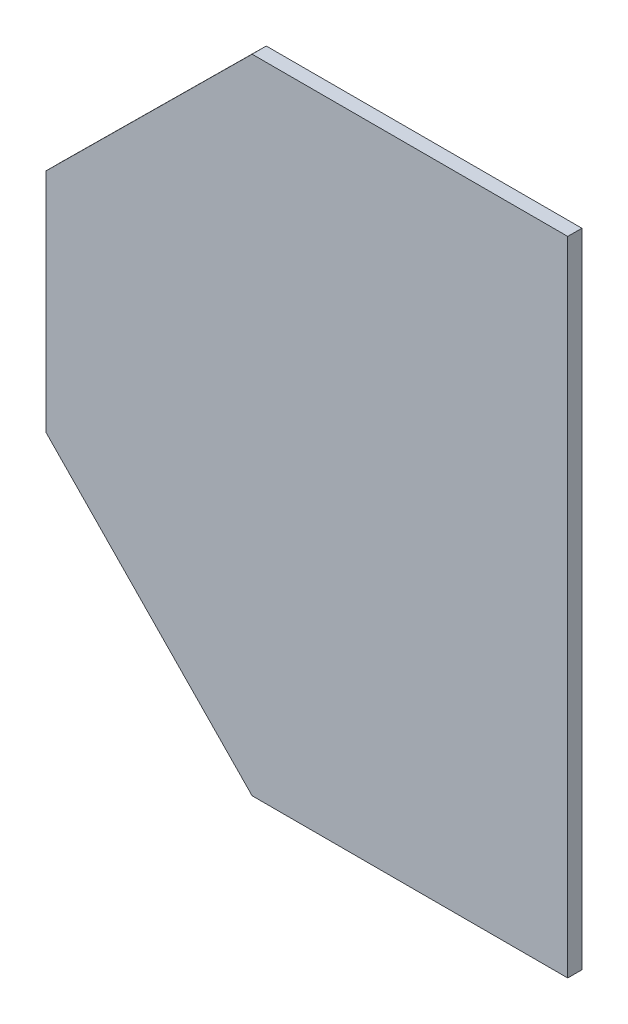
SolidWorks part; units mm, degrees
material "ASTM A500 Grade B"
ref_plane "Front Plane" through (0, 0, 0) normal (0, 0, 1) x (1, 0, 0)
ref_plane "Top Plane" through (0, 0, 0) normal (0, 1, 0) x (1, 0, 0)
ref_plane "Right Plane" through (0, 0, 0) normal (1, 0, 0) x (0, 0, -1)
sketch "Sketch1" plane through (0, 0, 0) normal (0, 0, 1) x (1, 0, 0)
  line L0 (-4.281, -146.7903) -> (-216.4881, -146.7903)
  line L1 (-4.281, -2487.2903) -> (-4.281, 2625.5097) construction
  line L2 (-216.4881, 285.0097) -> (-354.9957, 147.8379)
  line L4 (-354.9957, 147.8379) -> (-354.9957, -4.5621)
  line L6 (-354.9957, -4.5621) -> (-216.4881, -146.7903)
  line L7 (-216.4881, 285.0097) -> (-4.281, 285.0097)
  line L8 (-4.281, 285.0097) -> (-4.281, -146.7903)
  line L9 (-122.7465, 69.1097) -> (35.4026, 69.1097) construction
  line L10 (-122.7465, 119.9097) -> (-122.7465, 18.3097) construction
  dimension "D1" = 215.9
  dimension "D2" = 215.9
  dimension "D3" = 152.4
extrude "Boss-Extrude1" add sketch "Sketch1" along normal blind 9.525
